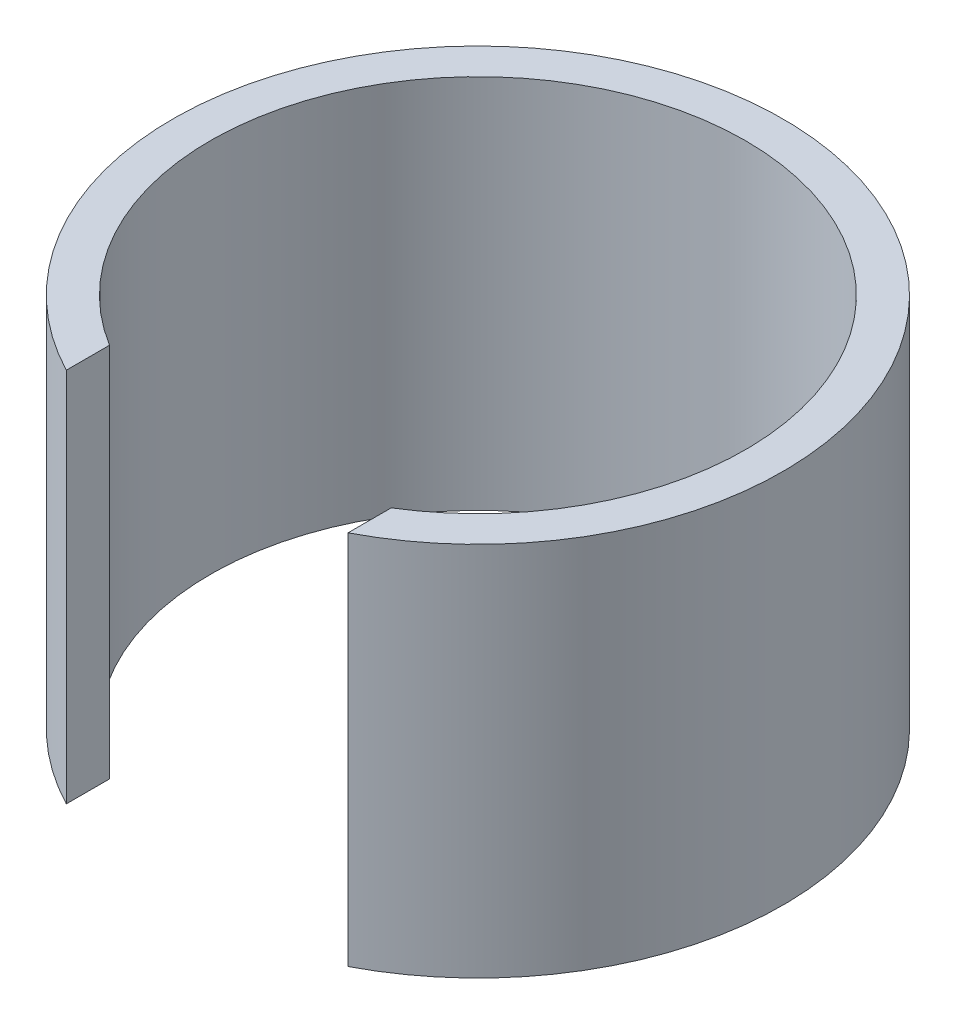
SolidWorks part; units mm, degrees
ref_plane "Plano frontal" through (0, 0, 0) normal (0, 0, 1) x (1, 0, 0)
ref_plane "Plano superior" through (0, 0, 0) normal (0, 1, 0) x (1, 0, 0)
ref_plane "Plano direito" through (0, 0, 0) normal (1, 0, 0) x (0, 0, -1)
sketch "Esboço2" plane through (0, 0, 0) normal (0, 1, 0) x (1, 0, 0)
  circle A0 centre (0, 0) radius 32.5
  dimension "D1" = 65
extrude "Ressalto-extrusão1" add sketch "Esboço2" along normal blind 40
sketch "Esboço3" plane through (0, 40, 0) normal (0, 1, 0) x (1, 0, 0)
  circle A0 centre (0, 0) radius 28.5
  circle A1 centre (0, 0) radius 32.5 construction
  dimension "D1" = 4
extrude "Corte-extrusão1" cut sketch "Esboço3" against normal blind 40
sketch "Esboço4" plane through (0, 0, 0) normal (0, 1, 0) x (1, 0, 0)
  line L1 (-15, -17.053) -> (15, -17.053)
  line L2 (-15, -17.053) -> (-15, -36.5422)
  line L3 (-15, -36.5422) -> (15, -36.5422)
  line L4 (15, -17.053) -> (15, -36.5422)
  point P4 (0, -17.053)
  dimension "D1" = 30
extrude "Corte-extrusão2" cut sketch "Esboço4" along normal through all
